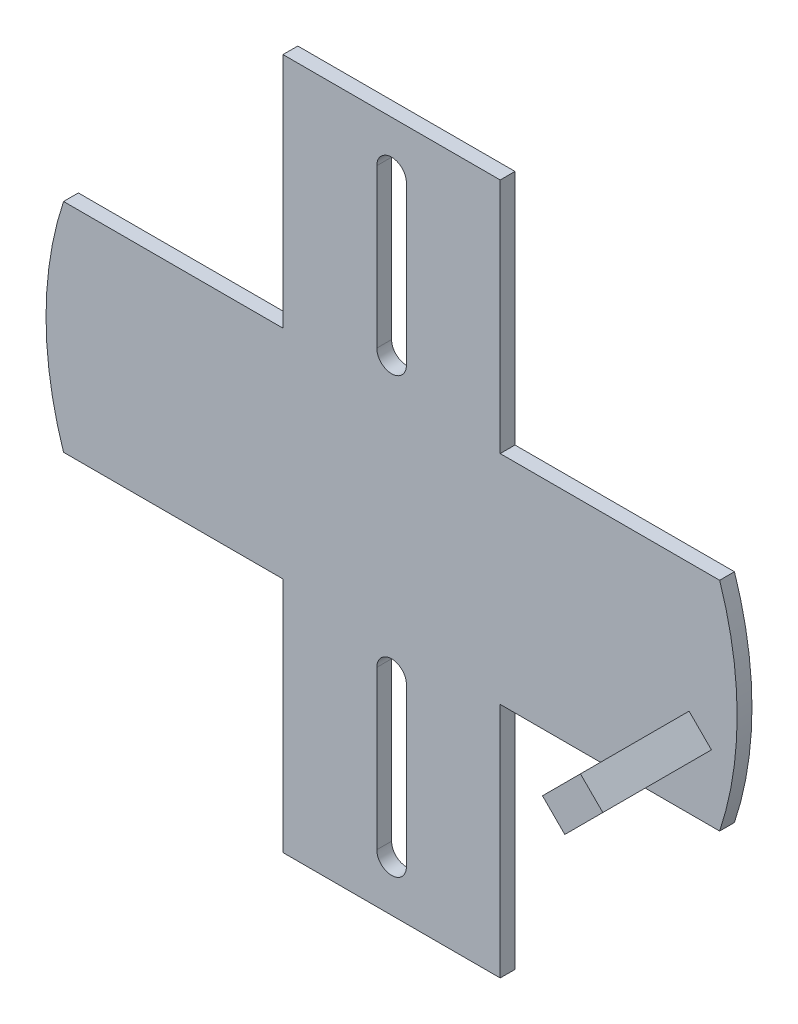
SolidWorks part; units mm, degrees
material "Epoxy, renforcé"
ref_plane "Plan de face" through (0, 0, 0) normal (0, 0, 1) x (1, 0, 0)
ref_plane "Plan de dessus" through (0, 0, 0) normal (0, 1, 0) x (1, 0, 0)
ref_plane "Plan de droite" through (0, 0, 0) normal (1, 0, 0) x (0, 0, -1)
sketch "Esquisse1" plane through (0, 0, 0) normal (0, 0, 1) x (1, 0, 0)
  line L0 (0, 5) -> (0, -11) construction
  line L1 (-11, 10) -> (11, 10)
  line L2 (11, 10) -> (11, -14)
  line L3 (11, -14) -> (33.2265, -14)
  line L5 (1.5, 5) -> (1.5, -11)
  line L6 (-1.5, 5) -> (-1.5, -11)
  line L7 (0, -39) -> (0, -55) construction
  line L8 (1.5, -39) -> (1.5, -55)
  line L9 (-1.5, -39) -> (-1.5, -55)
  line L11 (33.2265, -36) -> (11, -36)
  line L12 (11, -36) -> (11, -60)
  line L13 (11, -60) -> (-11, -60)
  line L14 (-11, -60) -> (-11, -36)
  line L15 (-11, -36) -> (-33.2265, -36)
  line L18 (-33.2265, -14) -> (-11, -14)
  line L19 (-11, -14) -> (-11, 10)
  arc A0 (1.5, 5) -> (-1.5, 5) centre (0, 5) ccw
  arc A1 (-1.5, -11) -> (1.5, -11) centre (0, -11) ccw
  arc A2 (1.5, -39) -> (-1.5, -39) centre (0, -39) ccw
  arc A3 (-1.5, -55) -> (1.5, -55) centre (0, -55) ccw
  arc A4 (-33.2265, -14) -> (-33.2265, -36) centre (0, -25) ccw
  arc A5 (33.2265, -14) -> (33.2265, -36) centre (0, -25) cw
  point P7 (0, -3)
  point P12 (0, -47)
  dimension "D1" = 22
  dimension "D8" = 35
  dimension "D9" = 35
  dimension "D2" = 1.5
  dimension "D3" = 1.5
  dimension "D4" = 11
  dimension "D5" = 70
  dimension "D6" = 22
  dimension "D7" = 11
  dimension "D10" = 16
  dimension "D11" = 16
extrude "Boss.-Extru.1" add sketch "Esquisse1" along normal blind 1.5
sketch "Esquisse2"
sketch "Esquisse3" plane through (0, 0, 1.5) normal (0, 0, 1) x (1, 0, 0)
  line L0 (28.5442, -33.14) -> (32.3928, -29.2913)
  line L1 (28.5442, -33.14) -> (26.2809, -30.8767)
  line L2 (32.3928, -29.2913) -> (30.1295, -27.028)
  line L3 (26.2809, -30.8767) -> (30.1295, -27.028)
  line L4 (11, -36) -> (33.2265, -36) construction
  dimension "D1" = 45
extrude "Boss.-Extru.2" add sketch "Esquisse3" along normal blind 11
